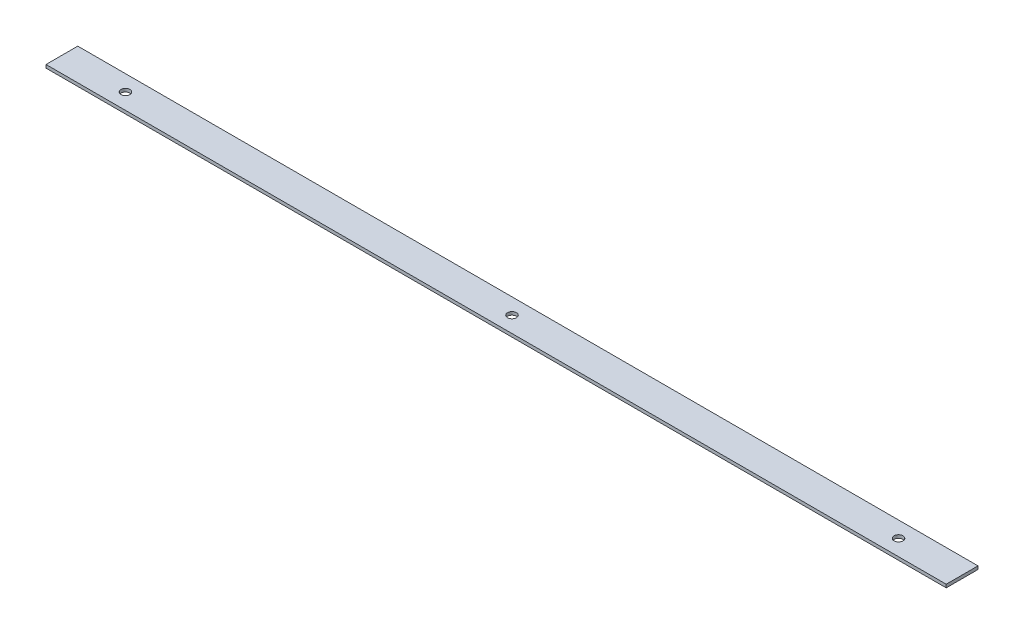
SolidWorks part; units mm, degrees
material "Galvanized Steel"
ref_plane "Front Plane" through (0, 0, 0) normal (0, 0, 1) x (1, 0, 0)
ref_plane "Top Plane" through (0, 0, 0) normal (0, 1, 0) x (1, 0, 0)
ref_plane "Right Plane" through (0, 0, 0) normal (1, 0, 0) x (0, 0, -1)
sketch "Sketch1" plane through (0, 0, 0) normal (0, 1, 0) x (1, 0, 0)
  line L1 (-354, -12.5) -> (354, -12.5)
  line L2 (-354, -12.5) -> (-354, 12.5)
  line L3 (-354, 12.5) -> (354, 12.5)
  line L4 (354, -12.5) -> (354, 12.5)
  line L5 (-354, -12.5) -> (354, 12.5) construction
  line L6 (-354, 12.5) -> (354, -12.5) construction
  point P0 (0, 0)
  dimension "D1" = 25
  dimension "D2" = 708
extrude "Boss-Extrude1" add sketch "Sketch1" along normal blind 2.5
sketch "Sketch2" plane through (0, 2.5, 0) normal (0, 1, 0) x (1, 0, 0)
  line L0 (-354, 12.5) -> (-354, -12.5) construction
  circle A0 centre (-304, 0) radius 3.5
  dimension "D1" = 7
  dimension "D2" = 50
extrude "Cut-Extrude1" cut sketch "Sketch2" against normal through all both and the other way through all
pattern_linear "LPattern1" count 3 spacing 304 along (1, 0, 0) of "Cut-Extrude1"
